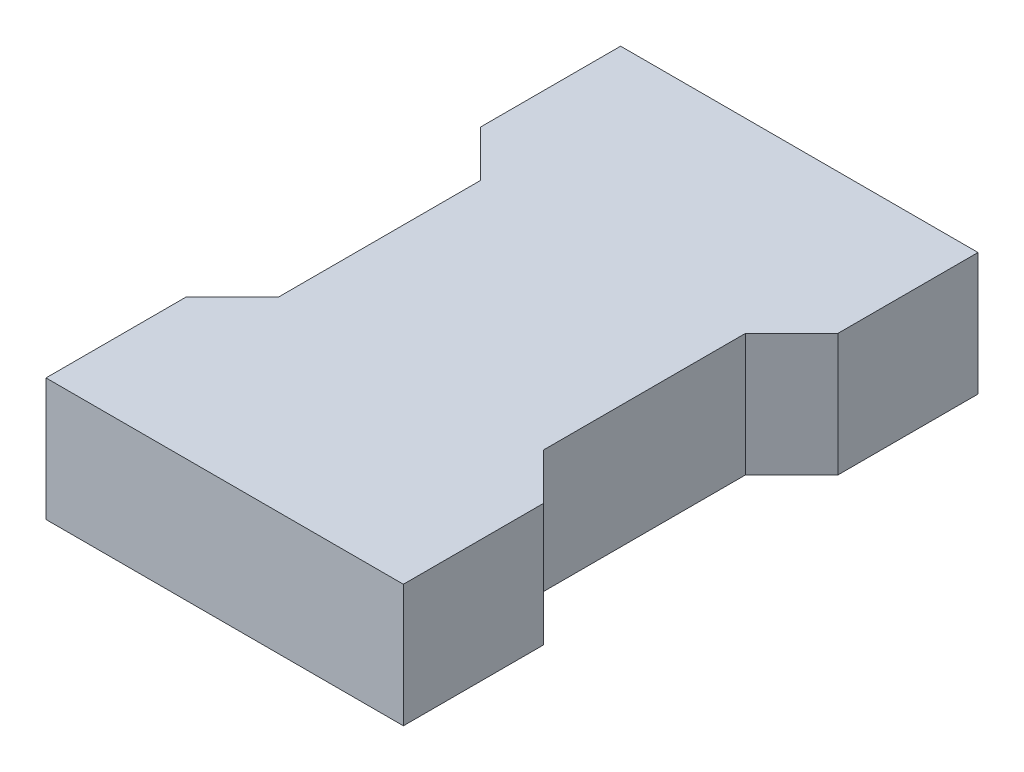
SolidWorks part; units mm, degrees
ref_plane "前视基准面" through (0, 0, 0) normal (0, 0, 1) x (1, 0, 0)
ref_plane "上视基准面" through (0, 0, 0) normal (0, 1, 0) x (1, 0, 0)
ref_plane "右视基准面" through (0, 0, 0) normal (1, 0, 0) x (0, 0, -1)
sketch "草图1" plane through (0, 0, 0) normal (0, 1, 0) x (1, 0, 0)
  line L0 (-25.5, 21) -> (-18.9026, 14.4026)
  line L1 (-25.5, 41) -> (25.5, 41)
  line L2 (-25.5, 41) -> (-25.5, 21)
  line L3 (-25.5, -41) -> (25.5, -41)
  line L4 (25.5, 41) -> (25.5, 21)
  line L5 (-25.5, 41) -> (25.5, -41) construction
  line L6 (-25.5, -41) -> (25.5, 41) construction
  line L7 (-18.9026, 14.4026) -> (-18.9026, -14.4026)
  line L8 (-18.9026, -14.4026) -> (-25.5, -21)
  line L9 (0, 53.9342) -> (0, -53.269) construction
  line L10 (18.9026, -14.4026) -> (25.5, -21)
  line L11 (25.5, 21) -> (18.9026, 14.4026)
  line L12 (18.9026, 14.4026) -> (18.9026, -14.4026)
  line L13 (-25.5, -21) -> (-25.5, -41)
  line L14 (25.5, -21) -> (25.5, -41)
  point P0 (0, 0)
  dimension "D1" = 51
  dimension "D2" = 82
  dimension "D3" = 20
  dimension "D4" = 20
  dimension "D5" = 45
extrude "凸台-拉伸1" add sketch "草图1" along normal blind 17.5
